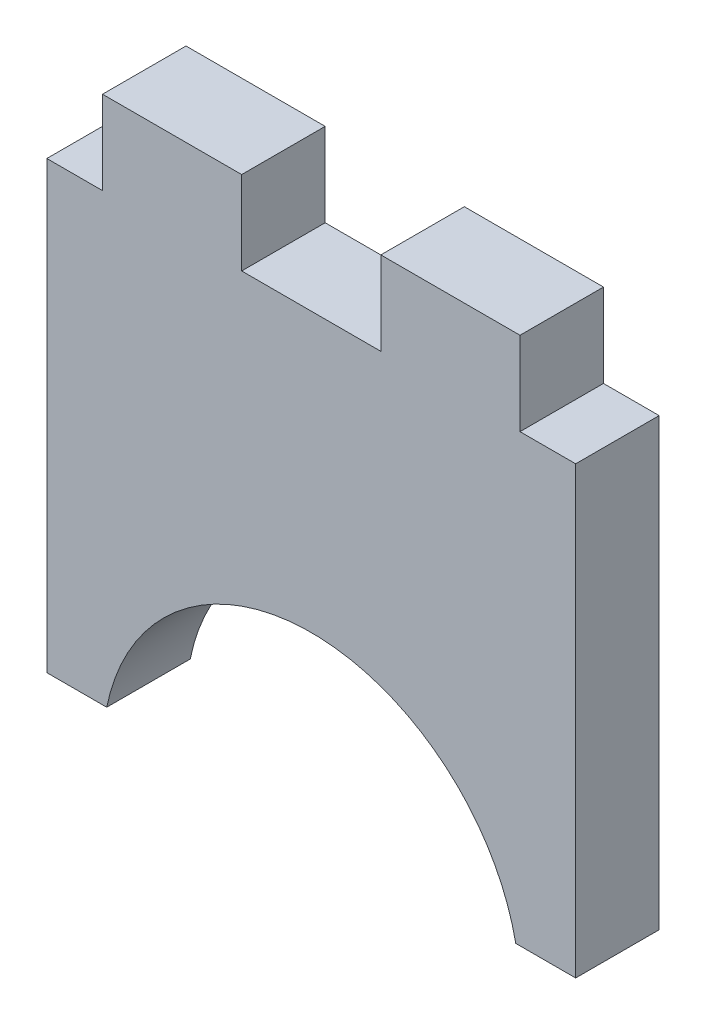
SolidWorks part; units mm, degrees
ref_plane "Front" through (0, 0, 0) normal (0, 0, 1) x (1, 0, 0)
ref_plane "Top" through (0, 0, 0) normal (0, 1, 0) x (1, 0, 0)
ref_plane "Right" through (0, 0, 0) normal (1, 0, 0) x (0, 0, -1)
sketch "Sketch1" plane through (0, 0, 0) normal (0, 0, 1) x (1, 0, 0)
  line L0 (-19, 41) -> (-19, 0) construction
  line L1 (0, 0) -> (-38, 0) construction
  line L2 (0, 0) -> (0, 41) construction
  line L3 (0, 41) -> (-38, 41) construction
  line L4 (-38, 0) -> (-38, 41) construction
  line L6 (0, 35) -> (-38, 35) construction
  line L7 (-4, 0) -> (-4, 41) construction
  line L8 (-34, 0) -> (-34, 41) construction
  line L9 (-24, 0) -> (-24, 41) construction
  line L10 (-14, 0) -> (-14, 41) construction
  line L11 (-38, 4) -> (-38, 35)
  line L12 (-38, 35) -> (-34, 35)
  line L13 (-34, 35) -> (-34, 41)
  line L14 (-34, 41) -> (-24, 41)
  line L15 (-24, 41) -> (-24, 35)
  line L16 (-24, 35) -> (-14, 35)
  line L17 (-14, 35) -> (-14, 41)
  line L18 (-14, 41) -> (-4, 41)
  line L19 (-4, 41) -> (-4, 35)
  line L20 (-4, 35) -> (0, 35)
  line L21 (0, 35) -> (0, 4)
  line L22 (-38, 4) -> (-38, 0)
  line L23 (-38, 0) -> (-34, 0)
  line L24 (0, 4) -> (0, 0)
  line L25 (0, 0) -> (-4, 0)
  line L26 (0, 3) -> (-38, 3)
  arc A0 (-4, 0) -> (-34, 0) centre (-19, 0) ccw
  dimension "D3" = 30
  dimension "D1" = 41
  dimension "D2" = 38
  dimension "D4" = 3
  dimension "D5" = 6
  dimension "D6" = 4
  dimension "D7" = 4
  dimension "D8" = 10
  dimension "D9" = 10
extrude "Boss-Extrude1" add sketch "Sketch1" along normal blind 6
